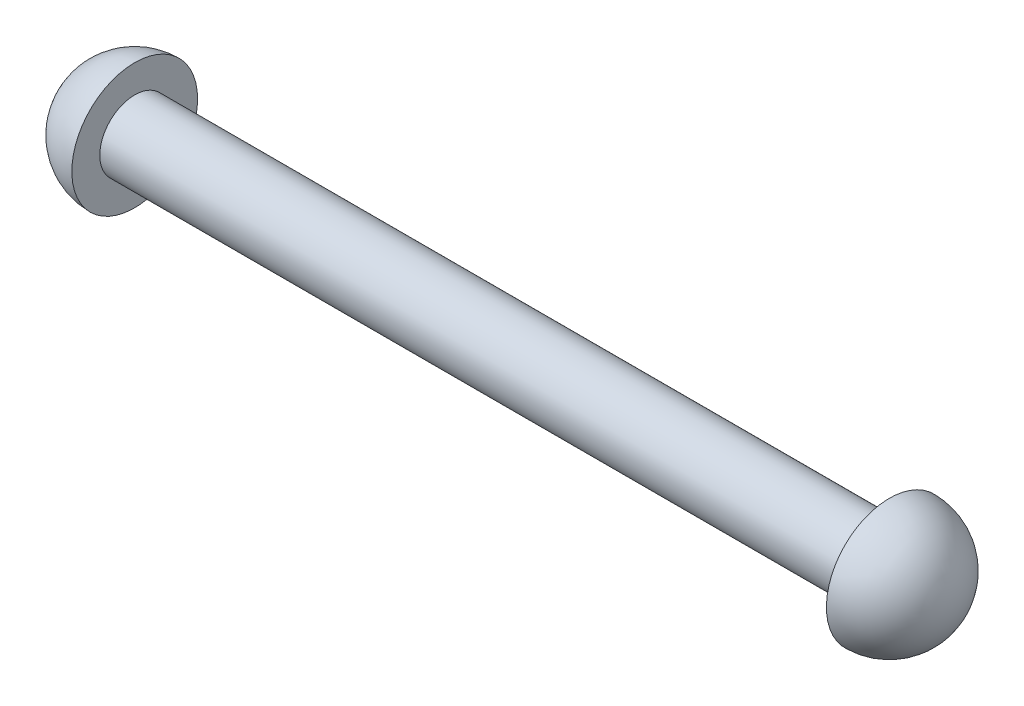
SolidWorks part; units mm, degrees
material "AISI 1020"
ref_plane "Front Plane" through (0, 0, 0) normal (0, 0, 1) x (1, 0, 0)
ref_plane "Top Plane" through (0, 0, 0) normal (0, 1, 0) x (1, 0, 0)
ref_plane "Right Plane" through (0, 0, 0) normal (1, 0, 0) x (0, 0, -1)
sketch "Sketch1" plane through (0, 0, 0) normal (0, 0, 1) x (1, 0, 0)
  line L0 (46.1455, 0) -> (0, 0) construction
  line L1 (0, 0) -> (0, 22.349) construction
  line L2 (-34.29, 3.175) -> (34.29, 3.175)
  line L3 (34.29, 3.175) -> (34.29, 5.715)
  line L4 (-34.29, 3.175) -> (-34.29, 5.715)
  line L5 (40.005, 0) -> (-40.005, 0)
  arc A0 (34.29, 5.715) -> (40.005, 0) centre (34.29, 0) cw
  arc A1 (-34.29, 5.715) -> (-40.005, 0) centre (-34.29, 0) ccw
  point P9 (0, 0)
  point P10 (46.1455, 0)
  point P15 (0, 3.175)
  dimension "D3" = 5.715
  dimension "D1" = 6.35
  dimension "D2" = 68.58
revolve "Revolve1" add sketch "Sketch1" angle 360 about L5
